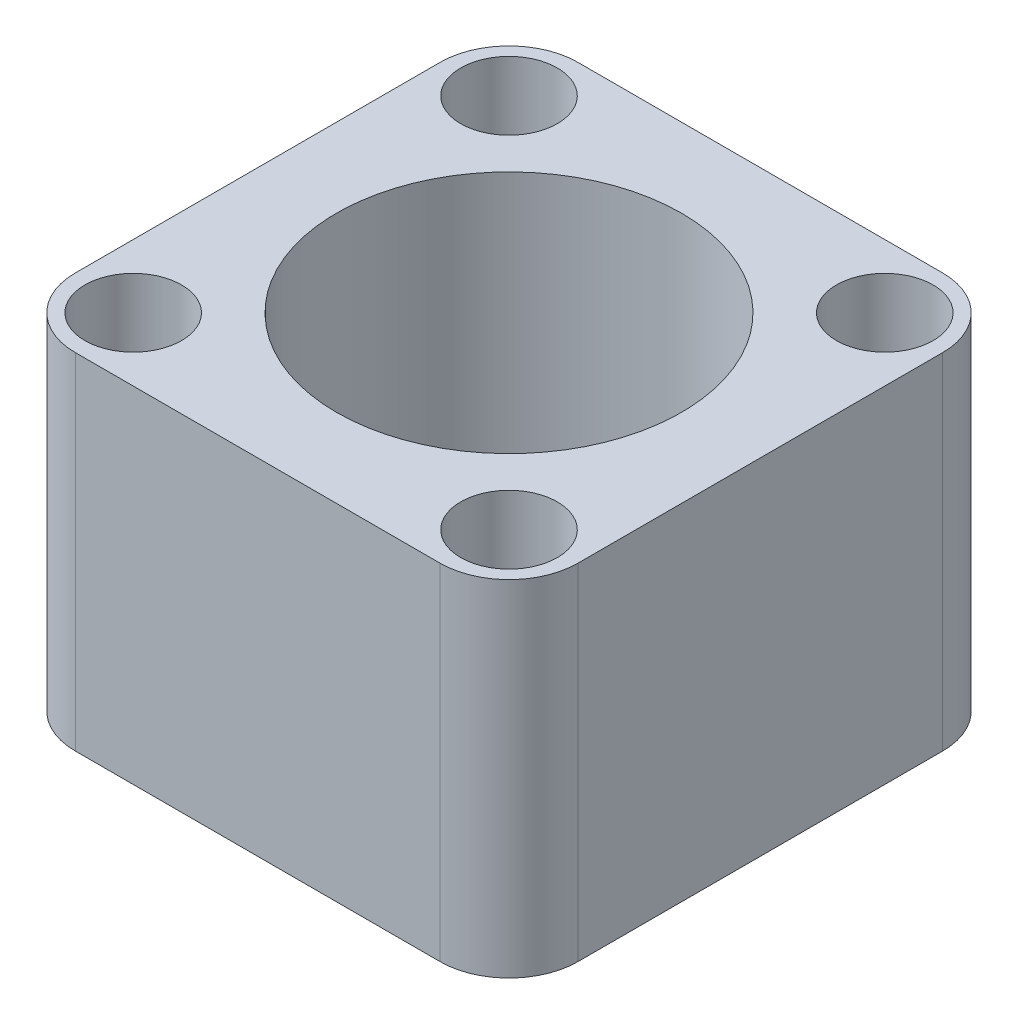
SolidWorks part; units mm, degrees
material "6061-T6 (SS)"
ref_plane "Front Plane" through (0, 0, 0) normal (0, 0, 1) x (1, 0, 0)
ref_plane "Top Plane" through (0, 0, 0) normal (0, 1, 0) x (1, 0, 0)
ref_plane "Right Plane" through (0, 0, 0) normal (1, 0, 0) x (0, 0, -1)
sketch "Sketch3" plane through (0, 0, 0) normal (0, 1, 0) x (1, 0, 0)
  line L1 (0, 0) -> (-18.4993, 0)
  line L2 (0, 0) -> (0, 18.4993)
  line L3 (0, 18.4993) -> (-18.4993, 18.4993)
  line L4 (-18.4993, 0) -> (-18.4993, 18.4993)
  dimension "D1" = 26.162
extrude "Boss-Extrude2" add sketch "Sketch3" along normal blind 12.7 contours L3 L4 L1 L2
fillet "Fillet2" radius 2.54 4 edges at (-18.4993, 6.35, 0) (0, 6.35, 0) (0, 6.35, -18.4993) (-18.4993, 6.35, -18.4993)
sketch "Sketch4" plane through (0, 12.7, 0) normal (0, 1, 0) x (1, 0, 0)
  line L0 (-9.2497, 0) -> (-9.2497, 18.4993) construction
  line L1 (-2.54, 0) -> (-15.9593, 0) construction
  line L2 (-2.54, 18.4993) -> (-15.9593, 18.4993) construction
  line L3 (0, 9.2497) -> (-18.4993, 9.2497) construction
  line L4 (0, 2.54) -> (0, 15.9593) construction
  line L5 (-18.4993, 2.54) -> (-18.4993, 15.9593) construction
  line L6 (-9.2497, 9.2497) -> (-2.3349, 2.3349) construction
  line L7 (-9.2497, 9.2497) -> (-16.1645, 2.3349) construction
  line L8 (-9.2497, 9.2497) -> (-2.3349, 16.1645) construction
  line L9 (-9.2497, 9.2497) -> (-16.1645, 16.1645) construction
  circle A0 centre (-9.2497, 9.2497) radius 6.35
  circle A1 centre (-2.3349, 2.3349) radius 1.778
  circle A2 centre (-16.1645, 2.3349) radius 1.778
  circle A3 centre (-16.1645, 16.1645) radius 1.778
  circle A4 centre (-2.3349, 16.1645) radius 1.778
  dimension "D1" = 12.7
  dimension "D2" = 9.779
  dimension "D3" = 3.556
extrude "Cut-Extrude1" cut sketch "Sketch4" against normal up to surface (12.7 mm away) up to face at (-9.2497, 0, -9.2497)
